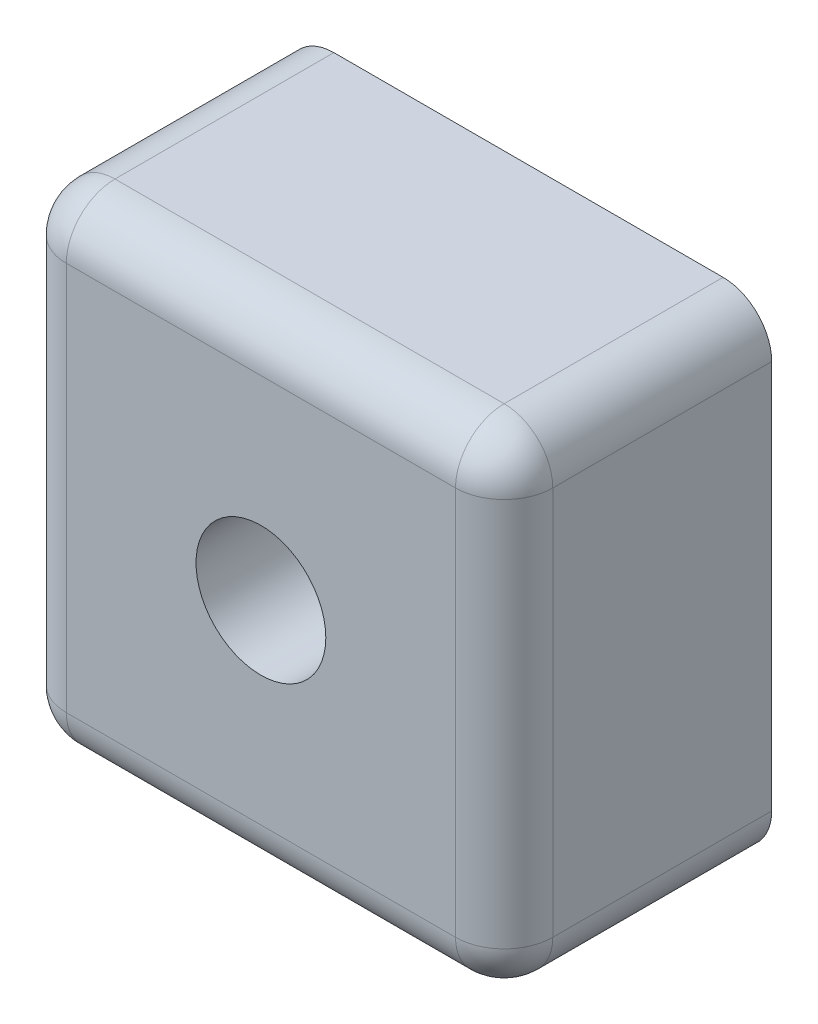
SolidWorks part; units mm, degrees
ref_plane "前视基准面" through (0, 0, 0) normal (0, 0, 1) x (1, 0, 0)
ref_plane "上视基准面" through (0, 0, 0) normal (0, 1, 0) x (1, 0, 0)
ref_plane "右视基准面" through (0, 0, 0) normal (1, 0, 0) x (0, 0, -1)
sketch "草图1" plane through (0, 0, 0) normal (0, 0, 1) x (1, 0, 0)
  line L0 (-50, -50) -> (50, -50)
  line L1 (0, 0) -> (50, 0)
  line L2 (0, -50) -> (0, 50)
  line L3 (-50, 50) -> (50, 50)
  line L4 (50, -50) -> (50, 50)
  line L5 (-50, -50) -> (-50, 50)
  circle A0 centre (0, 0) radius 13.3398
  circle A1 centre (0, 0) radius 28.3826
  dimension "D1" = 50
  dimension "D2" = 50
extrude "凸台-拉伸1" add sketch "草图1" along normal blind 55 contours A1 L2 L3 L5 L0 | A1 L1 L4 L3 L2 | L1 A1 L2 A0 | L2 A1 A0 | L2 A1 L1 A0 | A1 L2 L0 L4 L1
fillet "圆角2" radius 10 4 edges at (-50, -50, 27.5) (50, -50, 27.5) (50, 50, 27.5) (-50, 50, 27.5)
fillet "圆角3" radius 10 8 edges at (-47.0711, 47.0711, 55) (-50, 0, 55) (-47.0711, -47.0711, 55) (0, -50, 55) (47.0711, -47.0711, 55) (50, 0, 55) (47.0711, 47.0711, 55) (0, 50, 55)
